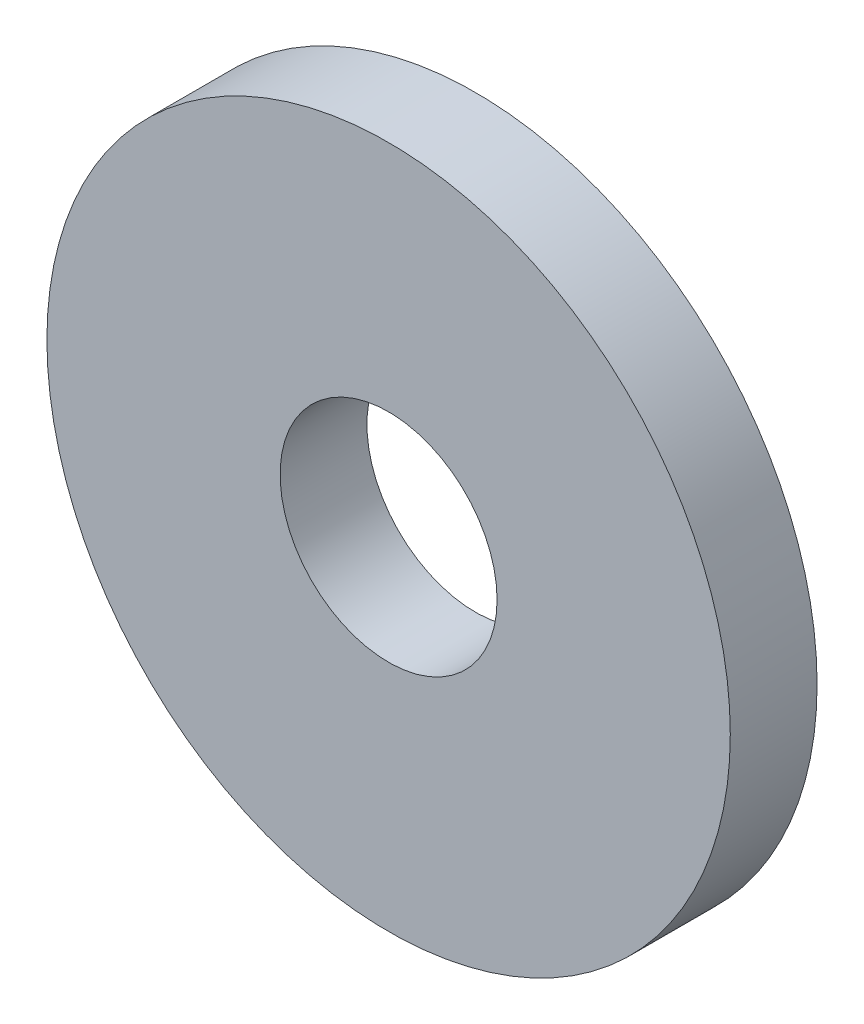
SolidWorks part; units mm, degrees
ref_plane "Front Plane" through (0, 0, 0) normal (0, 0, 1) x (1, 0, 0)
ref_plane "Top Plane" through (0, 0, 0) normal (0, 1, 0) x (1, 0, 0)
ref_plane "Right Plane" through (0, 0, 0) normal (1, 0, 0) x (0, 0, -1)
sketch "Sketch1" plane through (0, 0, 0) normal (0, 0, 1) x (1, 0, 0)
  circle A0 centre (0, 0) radius 25
  circle A1 centre (0, 0) radius 7.9375
  dimension "D1" = 50
  dimension "D2" = 15.875
extrude "Boss-Extrude1" add sketch "Sketch1" along normal blind 6.35
